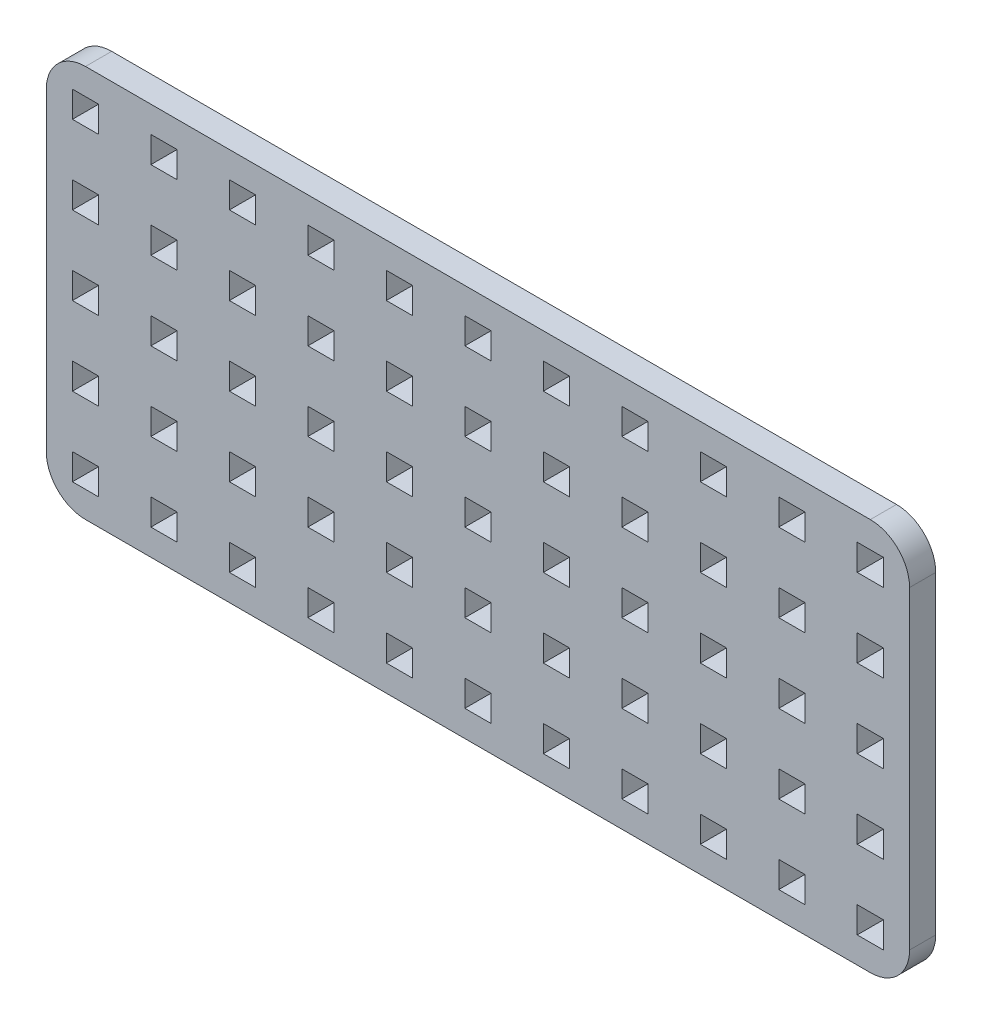
SolidWorks part; units mm, degrees
ref_plane "Alzado" through (0, 0, 0) normal (0, 0, 1) x (1, 0, 0)
ref_plane "Planta" through (0, 0, 0) normal (0, 1, 0) x (1, 0, 0)
ref_plane "Vista lateral" through (0, 0, 0) normal (1, 0, 0) x (0, 0, -1)
sketch "Model" plane through (0, 0, 0) normal (0, 0, 1) x (1, 0, 0)
  line L0 (8.4202, 297.2418) -> (8.4202, 294.2418)
  line L1 (11.4202, 297.2418) -> (8.4202, 297.2418)
  line L2 (11.4202, 294.2418) -> (11.4202, 297.2418)
  line L3 (8.4202, 294.2418) -> (11.4202, 294.2418)
  line L4 (17.4202, 297.2418) -> (17.4202, 294.2418)
  line L5 (20.4202, 297.2418) -> (17.4202, 297.2418)
  line L6 (20.4202, 294.2418) -> (20.4202, 297.2418)
  line L7 (17.4202, 294.2418) -> (20.4202, 294.2418)
  line L8 (26.4202, 297.2418) -> (26.4202, 294.2418)
  line L9 (29.4202, 297.2418) -> (26.4202, 297.2418)
  line L10 (29.4202, 294.2418) -> (29.4202, 297.2418)
  line L11 (26.4202, 294.2418) -> (29.4202, 294.2418)
  line L12 (35.4202, 297.2418) -> (35.4202, 294.2418)
  line L13 (38.4202, 297.2418) -> (35.4202, 297.2418)
  line L14 (38.4202, 294.2418) -> (38.4202, 297.2418)
  line L15 (35.4202, 294.2418) -> (38.4202, 294.2418)
  line L16 (44.4202, 297.2418) -> (44.4202, 294.2418)
  line L17 (47.4202, 297.2418) -> (44.4202, 297.2418)
  line L18 (47.4202, 294.2418) -> (47.4202, 297.2418)
  line L19 (44.4202, 294.2418) -> (47.4202, 294.2418)
  line L20 (53.4202, 297.2418) -> (53.4202, 294.2418)
  line L21 (56.4202, 297.2418) -> (53.4202, 297.2418)
  line L22 (56.4202, 294.2418) -> (56.4202, 297.2418)
  line L23 (53.4202, 294.2418) -> (56.4202, 294.2418)
  line L24 (62.4202, 297.2418) -> (62.4202, 294.2418)
  line L25 (65.4202, 297.2418) -> (62.4202, 297.2418)
  line L26 (65.4202, 294.2418) -> (65.4202, 297.2418)
  line L27 (62.4202, 294.2418) -> (65.4202, 294.2418)
  line L28 (71.4202, 297.2418) -> (71.4202, 294.2418)
  line L29 (74.4202, 297.2418) -> (71.4202, 297.2418)
  line L30 (74.4202, 294.2418) -> (74.4202, 297.2418)
  line L31 (71.4202, 294.2418) -> (74.4202, 294.2418)
  line L32 (80.4202, 297.2418) -> (80.4202, 294.2418)
  line L33 (83.4202, 297.2418) -> (80.4202, 297.2418)
  line L34 (83.4202, 294.2418) -> (83.4202, 297.2418)
  line L35 (80.4202, 294.2418) -> (83.4202, 294.2418)
  line L36 (89.4202, 297.2418) -> (89.4202, 294.2418)
  line L37 (92.4202, 297.2418) -> (89.4202, 297.2418)
  line L38 (92.4202, 294.2418) -> (92.4202, 297.2418)
  line L39 (89.4202, 294.2418) -> (92.4202, 294.2418)
  line L40 (98.4202, 297.2418) -> (98.4202, 294.2418)
  line L41 (101.4202, 297.2418) -> (98.4202, 297.2418)
  line L42 (101.4202, 294.2418) -> (101.4202, 297.2418)
  line L43 (98.4202, 294.2418) -> (101.4202, 294.2418)
  line L44 (8.4202, 261.2418) -> (8.4202, 258.2418)
  line L45 (11.4202, 261.2418) -> (8.4202, 261.2418)
  line L46 (11.4202, 258.2418) -> (11.4202, 261.2418)
  line L47 (8.4202, 258.2418) -> (11.4202, 258.2418)
  line L48 (17.4202, 261.2418) -> (17.4202, 258.2418)
  line L49 (20.4202, 261.2418) -> (17.4202, 261.2418)
  line L50 (20.4202, 258.2418) -> (20.4202, 261.2418)
  line L51 (17.4202, 258.2418) -> (20.4202, 258.2418)
  line L52 (26.4202, 261.2418) -> (26.4202, 258.2418)
  line L53 (29.4202, 261.2418) -> (26.4202, 261.2418)
  line L54 (29.4202, 258.2418) -> (29.4202, 261.2418)
  line L55 (26.4202, 258.2418) -> (29.4202, 258.2418)
  line L56 (35.4202, 261.2418) -> (35.4202, 258.2418)
  line L57 (38.4202, 261.2418) -> (35.4202, 261.2418)
  line L58 (38.4202, 258.2418) -> (38.4202, 261.2418)
  line L59 (35.4202, 258.2418) -> (38.4202, 258.2418)
  line L60 (44.4202, 261.2418) -> (44.4202, 258.2418)
  line L61 (47.4202, 261.2418) -> (44.4202, 261.2418)
  line L62 (47.4202, 258.2418) -> (47.4202, 261.2418)
  line L63 (44.4202, 258.2418) -> (47.4202, 258.2418)
  line L64 (53.4202, 261.2418) -> (53.4202, 258.2418)
  line L65 (56.4202, 261.2418) -> (53.4202, 261.2418)
  line L66 (56.4202, 258.2418) -> (56.4202, 261.2418)
  line L67 (53.4202, 258.2418) -> (56.4202, 258.2418)
  line L68 (62.4202, 261.2418) -> (62.4202, 258.2418)
  line L69 (65.4202, 261.2418) -> (62.4202, 261.2418)
  line L70 (65.4202, 258.2418) -> (65.4202, 261.2418)
  line L71 (62.4202, 258.2418) -> (65.4202, 258.2418)
  line L72 (71.4202, 261.2418) -> (71.4202, 258.2418)
  line L73 (74.4202, 261.2418) -> (71.4202, 261.2418)
  line L74 (74.4202, 258.2418) -> (74.4202, 261.2418)
  line L75 (71.4202, 258.2418) -> (74.4202, 258.2418)
  line L76 (80.4202, 261.2418) -> (80.4202, 258.2418)
  line L77 (83.4202, 261.2418) -> (80.4202, 261.2418)
  line L78 (83.4202, 258.2418) -> (83.4202, 261.2418)
  line L79 (80.4202, 258.2418) -> (83.4202, 258.2418)
  line L80 (89.4202, 261.2418) -> (89.4202, 258.2418)
  line L81 (92.4202, 261.2418) -> (89.4202, 261.2418)
  line L82 (92.4202, 258.2418) -> (92.4202, 261.2418)
  line L83 (89.4202, 258.2418) -> (92.4202, 258.2418)
  line L84 (98.4202, 261.2418) -> (98.4202, 258.2418)
  line L85 (101.4202, 261.2418) -> (98.4202, 261.2418)
  line L86 (101.4202, 258.2418) -> (101.4202, 261.2418)
  line L87 (98.4202, 258.2418) -> (101.4202, 258.2418)
  line L88 (98.4202, 288.2418) -> (98.4202, 285.2418)
  line L89 (101.4202, 288.2418) -> (98.4202, 288.2418)
  line L90 (101.4202, 285.2418) -> (101.4202, 288.2418)
  line L91 (98.4202, 285.2418) -> (101.4202, 285.2418)
  line L92 (98.4202, 270.2418) -> (98.4202, 267.2418)
  line L93 (101.4202, 270.2418) -> (98.4202, 270.2418)
  line L94 (101.4202, 267.2418) -> (101.4202, 270.2418)
  line L95 (98.4202, 267.2418) -> (101.4202, 267.2418)
  line L96 (98.4202, 279.2418) -> (98.4202, 276.2418)
  line L97 (101.4202, 279.2418) -> (98.4202, 279.2418)
  line L98 (101.4202, 276.2418) -> (101.4202, 279.2418)
  line L99 (98.4202, 276.2418) -> (101.4202, 276.2418)
  line L100 (80.4202, 288.2418) -> (80.4202, 285.2418)
  line L101 (83.4202, 288.2418) -> (80.4202, 288.2418)
  line L102 (83.4202, 285.2418) -> (83.4202, 288.2418)
  line L103 (80.4202, 285.2418) -> (83.4202, 285.2418)
  line L104 (80.4202, 270.2418) -> (80.4202, 267.2418)
  line L105 (83.4202, 270.2418) -> (80.4202, 270.2418)
  line L106 (83.4202, 267.2418) -> (83.4202, 270.2418)
  line L107 (80.4202, 267.2418) -> (83.4202, 267.2418)
  line L108 (80.4202, 279.2418) -> (80.4202, 276.2418)
  line L109 (83.4202, 279.2418) -> (80.4202, 279.2418)
  line L110 (83.4202, 276.2418) -> (83.4202, 279.2418)
  line L111 (80.4202, 276.2418) -> (83.4202, 276.2418)
  line L112 (89.4202, 288.2418) -> (89.4202, 285.2418)
  line L113 (92.4202, 288.2418) -> (89.4202, 288.2418)
  line L114 (92.4202, 285.2418) -> (92.4202, 288.2418)
  line L115 (89.4202, 285.2418) -> (92.4202, 285.2418)
  line L116 (89.4202, 270.2418) -> (89.4202, 267.2418)
  line L117 (92.4202, 270.2418) -> (89.4202, 270.2418)
  line L118 (92.4202, 267.2418) -> (92.4202, 270.2418)
  line L119 (89.4202, 267.2418) -> (92.4202, 267.2418)
  line L120 (89.4202, 279.2418) -> (89.4202, 276.2418)
  line L121 (92.4202, 279.2418) -> (89.4202, 279.2418)
  line L122 (92.4202, 276.2418) -> (92.4202, 279.2418)
  line L123 (89.4202, 276.2418) -> (92.4202, 276.2418)
  line L124 (8.4202, 288.2418) -> (8.4202, 285.2418)
  line L125 (11.4202, 288.2418) -> (8.4202, 288.2418)
  line L126 (11.4202, 285.2418) -> (11.4202, 288.2418)
  line L127 (8.4202, 285.2418) -> (11.4202, 285.2418)
  line L128 (8.4202, 270.2418) -> (8.4202, 267.2418)
  line L129 (11.4202, 270.2418) -> (8.4202, 270.2418)
  line L130 (11.4202, 267.2418) -> (11.4202, 270.2418)
  line L131 (8.4202, 267.2418) -> (11.4202, 267.2418)
  line L132 (8.4202, 279.2418) -> (8.4202, 276.2418)
  line L133 (11.4202, 279.2418) -> (8.4202, 279.2418)
  line L134 (11.4202, 276.2418) -> (11.4202, 279.2418)
  line L135 (8.4202, 276.2418) -> (11.4202, 276.2418)
  line L136 (17.4202, 270.2418) -> (17.4202, 267.2418)
  line L137 (20.4202, 270.2418) -> (17.4202, 270.2418)
  line L138 (20.4202, 267.2418) -> (20.4202, 270.2418)
  line L139 (17.4202, 267.2418) -> (20.4202, 267.2418)
  line L140 (26.4202, 270.2418) -> (26.4202, 267.2418)
  line L141 (29.4202, 270.2418) -> (26.4202, 270.2418)
  line L142 (29.4202, 267.2418) -> (29.4202, 270.2418)
  line L143 (26.4202, 267.2418) -> (29.4202, 267.2418)
  line L144 (35.4202, 270.2418) -> (35.4202, 267.2418)
  line L145 (38.4202, 270.2418) -> (35.4202, 270.2418)
  line L146 (38.4202, 267.2418) -> (38.4202, 270.2418)
  line L147 (35.4202, 267.2418) -> (38.4202, 267.2418)
  line L148 (62.4202, 270.2418) -> (62.4202, 267.2418)
  line L149 (65.4202, 270.2418) -> (62.4202, 270.2418)
  line L150 (65.4202, 267.2418) -> (65.4202, 270.2418)
  line L151 (62.4202, 267.2418) -> (65.4202, 267.2418)
  line L152 (71.4202, 270.2418) -> (71.4202, 267.2418)
  line L153 (74.4202, 270.2418) -> (71.4202, 270.2418)
  line L154 (74.4202, 267.2418) -> (74.4202, 270.2418)
  line L155 (71.4202, 267.2418) -> (74.4202, 267.2418)
  line L156 (44.4202, 270.2418) -> (44.4202, 267.2418)
  line L157 (47.4202, 270.2418) -> (44.4202, 270.2418)
  line L158 (47.4202, 267.2418) -> (47.4202, 270.2418)
  line L159 (44.4202, 267.2418) -> (47.4202, 267.2418)
  line L160 (53.4202, 270.2418) -> (53.4202, 267.2418)
  line L161 (56.4202, 270.2418) -> (53.4202, 270.2418)
  line L162 (56.4202, 267.2418) -> (56.4202, 270.2418)
  line L163 (53.4202, 267.2418) -> (56.4202, 267.2418)
  line L164 (17.4202, 279.2418) -> (17.4202, 276.2418)
  line L165 (20.4202, 279.2418) -> (17.4202, 279.2418)
  line L166 (20.4202, 276.2418) -> (20.4202, 279.2418)
  line L167 (17.4202, 276.2418) -> (20.4202, 276.2418)
  line L168 (26.4202, 279.2418) -> (26.4202, 276.2418)
  line L169 (29.4202, 279.2418) -> (26.4202, 279.2418)
  line L170 (29.4202, 276.2418) -> (29.4202, 279.2418)
  line L171 (26.4202, 276.2418) -> (29.4202, 276.2418)
  line L172 (35.4202, 279.2418) -> (35.4202, 276.2418)
  line L173 (38.4202, 279.2418) -> (35.4202, 279.2418)
  line L174 (38.4202, 276.2418) -> (38.4202, 279.2418)
  line L175 (35.4202, 276.2418) -> (38.4202, 276.2418)
  line L176 (62.4202, 279.2418) -> (62.4202, 276.2418)
  line L177 (65.4202, 279.2418) -> (62.4202, 279.2418)
  line L178 (65.4202, 276.2418) -> (65.4202, 279.2418)
  line L179 (62.4202, 276.2418) -> (65.4202, 276.2418)
  line L180 (71.4202, 279.2418) -> (71.4202, 276.2418)
  line L181 (74.4202, 279.2418) -> (71.4202, 279.2418)
  line L182 (74.4202, 276.2418) -> (74.4202, 279.2418)
  line L183 (71.4202, 276.2418) -> (74.4202, 276.2418)
  line L184 (17.4202, 288.2418) -> (17.4202, 285.2418)
  line L185 (20.4202, 288.2418) -> (17.4202, 288.2418)
  line L186 (20.4202, 285.2418) -> (20.4202, 288.2418)
  line L187 (17.4202, 285.2418) -> (20.4202, 285.2418)
  line L188 (26.4202, 288.2418) -> (26.4202, 285.2418)
  line L189 (29.4202, 288.2418) -> (26.4202, 288.2418)
  line L190 (29.4202, 285.2418) -> (29.4202, 288.2418)
  line L191 (26.4202, 285.2418) -> (29.4202, 285.2418)
  line L192 (35.4202, 288.2418) -> (35.4202, 285.2418)
  line L193 (38.4202, 288.2418) -> (35.4202, 288.2418)
  line L194 (38.4202, 285.2418) -> (38.4202, 288.2418)
  line L195 (35.4202, 285.2418) -> (38.4202, 285.2418)
  line L196 (62.4202, 288.2418) -> (62.4202, 285.2418)
  line L197 (65.4202, 288.2418) -> (62.4202, 288.2418)
  line L198 (65.4202, 285.2418) -> (65.4202, 288.2418)
  line L199 (62.4202, 285.2418) -> (65.4202, 285.2418)
  line L200 (71.4202, 288.2418) -> (71.4202, 285.2418)
  line L201 (74.4202, 288.2418) -> (71.4202, 288.2418)
  line L202 (74.4202, 285.2418) -> (74.4202, 288.2418)
  line L203 (71.4202, 285.2418) -> (74.4202, 285.2418)
  line L204 (44.4202, 279.2418) -> (44.4202, 276.2418)
  line L205 (47.4202, 279.2418) -> (44.4202, 279.2418)
  line L206 (47.4202, 276.2418) -> (47.4202, 279.2418)
  line L207 (44.4202, 276.2418) -> (47.4202, 276.2418)
  line L208 (53.4202, 279.2418) -> (53.4202, 276.2418)
  line L209 (56.4202, 279.2418) -> (53.4202, 279.2418)
  line L210 (56.4202, 276.2418) -> (56.4202, 279.2418)
  line L211 (53.4202, 276.2418) -> (56.4202, 276.2418)
  line L212 (44.4202, 288.2418) -> (44.4202, 285.2418)
  line L213 (47.4202, 288.2418) -> (44.4202, 288.2418)
  line L214 (47.4202, 285.2418) -> (47.4202, 288.2418)
  line L215 (44.4202, 285.2418) -> (47.4202, 285.2418)
  line L216 (53.4202, 288.2418) -> (53.4202, 285.2418)
  line L217 (56.4202, 288.2418) -> (53.4202, 288.2418)
  line L218 (56.4202, 285.2418) -> (56.4202, 288.2418)
  line L219 (53.4202, 285.2418) -> (56.4202, 285.2418)
  line L220 (104.4202, 259.7418) -> (104.4202, 295.7418)
  line L221 (99.9202, 300.2418) -> (9.9202, 300.2418)
  line L222 (5.4202, 295.7418) -> (5.4202, 259.7418)
  line L223 (9.9202, 255.2418) -> (99.9202, 255.2418)
  arc A0 (104.4202, 295.7418) -> (99.9202, 300.2418) centre (99.9202, 295.7418) ccw
  arc A1 (99.9202, 255.2418) -> (104.4202, 259.7418) centre (99.9202, 259.7418) ccw
  arc A2 (9.9202, 300.2418) -> (5.4202, 295.7418) centre (9.9202, 295.7418) ccw
  arc A3 (5.4202, 259.7418) -> (9.9202, 255.2418) centre (9.9202, 259.7418) ccw
extrude "Saliente-Extruir1" add sketch "Model" along normal blind 3
